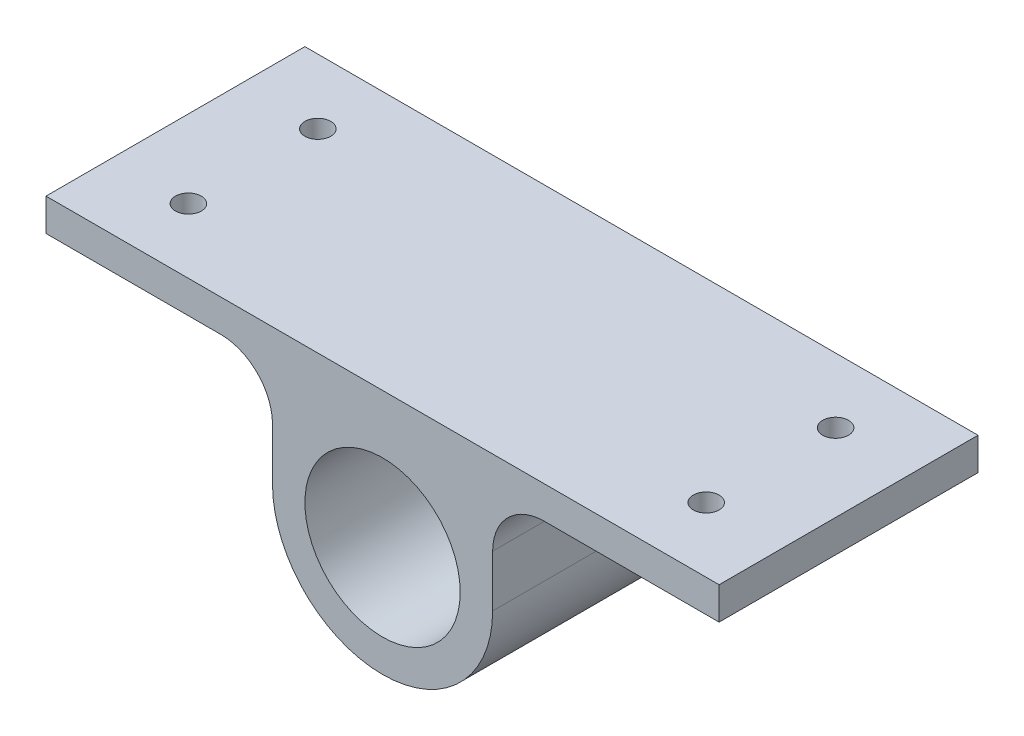
SolidWorks part; units mm, degrees
material "AISI 1020"
ref_plane "Front Plane" through (0, 0, 0) normal (0, 0, 1) x (1, 0, 0)
ref_plane "Top Plane" through (0, 0, 0) normal (0, 1, 0) x (1, 0, 0)
ref_plane "Right Plane" through (0, 0, 0) normal (1, 0, 0) x (0, 0, -1)
sketch "Sketch1" plane through (0, 0, 0) normal (0, 0, 1) x (1, 0, 0)
  line L0 (-82.55, 33.3502) -> (-82.55, 25.4)
  line L1 (-82.55, 25.4) -> (-39.7002, 25.4)
  line L2 (82.55, 33.3502) -> (-82.55, 33.3502)
  line L3 (82.55, 33.3502) -> (82.55, 25.4)
  line L4 (82.55, 25.4) -> (39.7002, 25.4)
  line L5 (-27.0002, 12.7) -> (-27.0002, 0)
  line L6 (27.0002, 12.7) -> (27.0002, 0)
  circle A0 centre (0, 0) radius 19.05
  arc A4 (-27.0002, 12.7) -> (-39.7002, 25.4) centre (-39.7002, 12.7) ccw
  arc A5 (39.7002, 25.4) -> (27.0002, 12.7) centre (39.7002, 12.7) ccw
  arc A6 (-27.0002, 0) -> (27.0002, 0) centre (0, 0) ccw
  point P18 (0, 0)
  point P19 (0, 0)
  point P20 (0, 0)
  dimension "D1" = 38.1
  dimension "D3" = 54.0004
  dimension "D4" = 25.4
  dimension "D5" = 25.4
  dimension "D2" = 165.1
  dimension "D6" = 33.3502
  dimension "D7" = 7.9502
  dimension "D8" = 7.9502
  dimension "D9" = 82.55
  dimension "D10" = 12.7
  dimension "D11" = 12.7
extrude "Boss-Extrude1" add sketch "Sketch1" along normal mid plane 63.5
sketch "Sketch2" plane through (0, 33.3502, 0) normal (0, 1, 0) x (1, 0, 0)
  line L0 (0, -11.2652) -> (0, 44.6174) construction
  line L1 (82.55, 31.75) -> (-82.55, 31.75) construction
  line L2 (-82.55, -31.75) -> (-82.55, 31.75) construction
  circle A0 centre (-63.5, 15.875) radius 3.175
  circle A1 centre (-63.5, -15.875) radius 3.175
  circle A2 centre (63.5, -15.875) radius 3.175
  circle A3 centre (63.5, 15.875) radius 3.175
  dimension "D1" = 6.35
  dimension "D2" = 15.875
  dimension "D4" = 31.75
  dimension "D3" = 19.05
  dimension "D5" = 19.05
extrude "Cut-Extrude1" cut sketch "Sketch2" against normal through all
